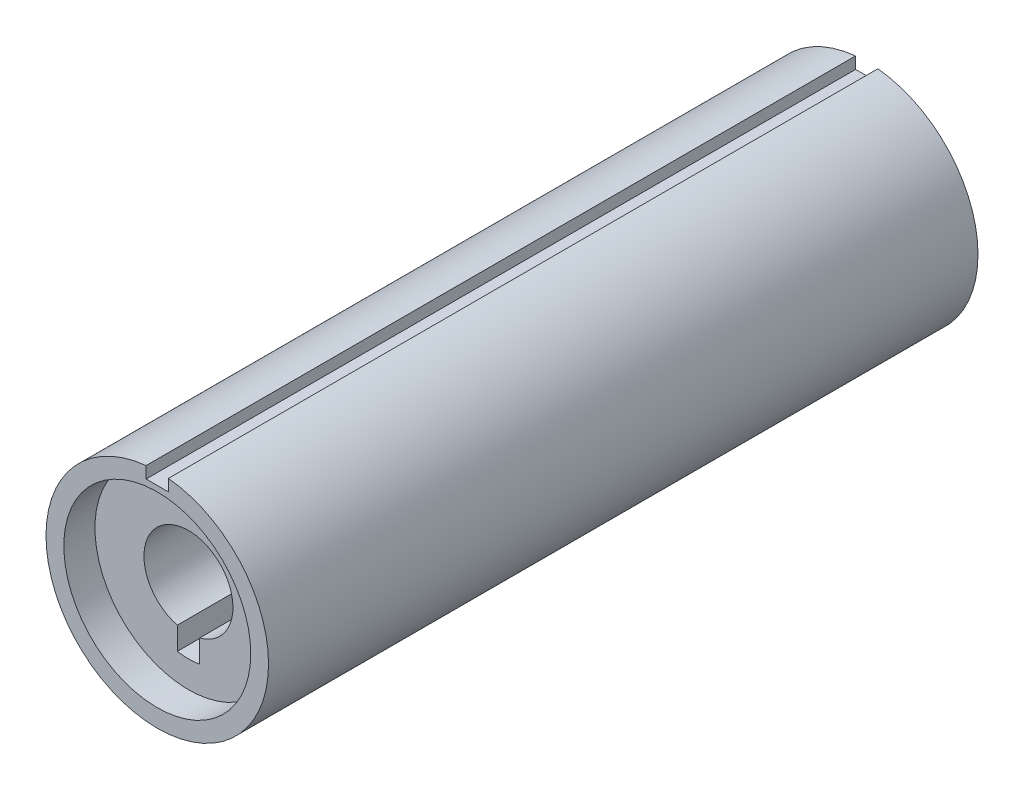
SolidWorks part; units mm, degrees
ref_plane "Front Plane" through (0, 0, 0) normal (0, 0, 1) x (1, 0, 0)
ref_plane "Top Plane" through (0, 0, 0) normal (0, 1, 0) x (1, 0, 0)
ref_plane "Right Plane" through (0, 0, 0) normal (1, 0, 0) x (0, 0, -1)
sketch "Sketch1" plane through (0, 0, 0) normal (0, 0, 1) x (1, 0, 0)
  line L3 (-2.5, 24.8747) -> (-2.5, 22.25)
  line L4 (-2.5, 22.25) -> (2.5, 22.25)
  line L5 (2.5, 22.25) -> (2.5, 24.8747)
  line L8 (-2.5, -9.6825) -> (-2.5, -25)
  line L9 (-2.5, -25) -> (2.5, -25)
  line L10 (2.5, -9.6825) -> (2.5, -25)
  arc A0 (-2.5, 24.8747) -> (2.5, 24.8747) centre (0, 0) ccw
  arc A1 (2.5, -9.6825) -> (-2.5, -9.6825) centre (0, 0) ccw
  point P12 (0, 22.25)
  point P13 (0, -25)
  dimension "D1" = 20
  dimension "D2" = 50
  dimension "D3" = 5
  dimension "D5" = 22.25
extrude "Boss-Extrude1" add sketch "Sketch1" along normal blind 152.4 contours A1 L10 A0 L5 L4 L3 L8
sketch "Sketch3" plane through (0, 0, 152.4) normal (0, 0, 1) x (1, 0, 0)
  line L6 (-2.5, 22.25) -> (2.5, 22.25)
  line L8 (-2.5, 22.25) -> (-2.5, 24.8747)
  line L10 (2.5, 22.25) -> (2.5, 24.8747)
  circle A0 centre (0, 0) radius 21
  arc A1 (-2.5, -24.8747) -> (2.5, 24.8747) centre (0, 0) ccw
  arc A3 (-2.5, 24.8747) -> (-2.5, -24.8747) centre (0, 0) ccw
  arc A4 (-2.5, 24.8747) -> (-2.5, -24.8747) centre (0, 0) ccw construction
  dimension "D1" = 42
extrude "Boss-Extrude2" add sketch "Sketch3" along normal blind 7
sketch "Sketch4" plane through (0, 0, 152.4) normal (0, 0, 1) x (1, 0, 0)
  line L0 (2.5, -9.6825) -> (2.5, -20.8507) construction
  line L2 (-2.5, -14.7902) -> (-2.5, -24.8747)
  line L3 (2.5, -24.8747) -> (2.5, -14.7902)
  line L4 (-2.5, -9.6825) -> (-2.5, -20.8507) construction
  arc A0 (-2.5, -14.7902) -> (2.5, -14.7902) centre (0, 0) ccw
  arc A1 (-2.5, -9.6825) -> (2.5, -9.6825) centre (0, 0) ccw construction
  arc A2 (-2.5, -24.8747) -> (2.5, -24.8747) centre (0, 0) ccw
  arc A3 (-2.5, 24.8747) -> (2.5, 24.8747) centre (0, 0) ccw construction
  point P8 (0, -10)
  point P12 (0, -15)
  dimension "D1" = 5
extrude "Boss-Extrude3" add sketch "Sketch4" against normal up to surface (152.4 mm away) up to face at (0, 5.6022, 0)
